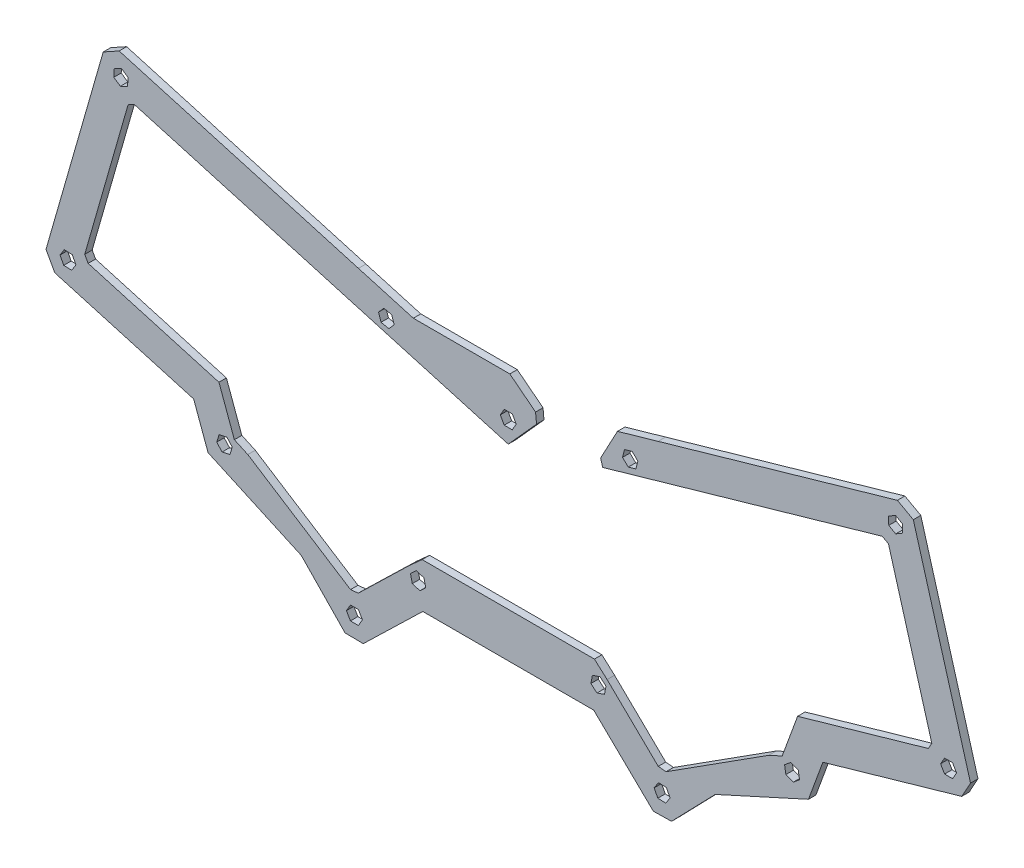
SolidWorks part; units mm, degrees
ref_plane "Plan de face" through (0, 0, 0) normal (0, 0, 1) x (1, 0, 0)
ref_plane "Plan de dessus" through (0, 0, 0) normal (0, 1, 0) x (1, 0, 0)
ref_plane "Plan de droite" through (0, 0, 0) normal (1, 0, 0) x (0, 0, -1)
sketch "Esquisse1" plane through (0, 0, 0) normal (0, 0, 1) x (1, 0, 0)
  line L0 (-121.6461, -32.0475) -> (-108.1875, -28.1884) construction
  line L1 (-108.1875, -28.1884) -> (-104.3283, -41.647) construction
  line L2 (-104.3283, -41.647) -> (-117.7869, -45.5062) construction
  line L3 (-117.7869, -45.5062) -> (-121.6461, -32.0475) construction
  line L4 (-100.1763, -37.9855) -> (-104.0355, -24.5269) construction
  line L5 (-104.0355, -24.5269) -> (-90.5769, -20.6677) construction
  line L6 (-90.5769, -20.6677) -> (-86.7177, -34.1263) construction
  line L7 (-86.7177, -34.1263) -> (-100.1763, -37.9855) construction
  line L8 (-82.5657, -30.4649) -> (-86.4249, -17.0063) construction
  line L9 (-86.4249, -17.0063) -> (-72.9663, -13.1471) construction
  line L10 (-72.9663, -13.1471) -> (-69.1071, -26.6057) construction
  line L11 (-69.1071, -26.6057) -> (-82.5657, -30.4649) construction
  line L12 (-63.6458, -27.5106) -> (-67.505, -14.0519) construction
  line L13 (-67.505, -14.0519) -> (-54.0463, -10.1927) construction
  line L14 (-54.0463, -10.1927) -> (-50.1872, -23.6514) construction
  line L15 (-50.1872, -23.6514) -> (-63.6458, -27.5106) construction
  line L16 (-44.0711, -26.8394) -> (-47.9303, -13.3808) construction
  line L17 (-47.9303, -13.3808) -> (-34.4717, -9.5216) construction
  line L18 (-34.4717, -9.5216) -> (-30.6125, -22.9802) construction
  line L19 (-30.6125, -22.9802) -> (-44.0711, -26.8394) construction
  line L20 (-25.8054, -21.6018) -> (-29.6646, -8.1432) construction
  line L21 (-29.6646, -8.1432) -> (-16.206, -4.284)
  line L22 (-16.206, -4.284) -> (-12.3468, -17.7426)
  line L23 (-12.3468, -17.7426) -> (-25.8054, -21.6018) construction
  line L24 (-116.4086, -50.3128) -> (-102.95, -46.4536) construction
  line L25 (-102.95, -46.4536) -> (-99.0908, -59.9122) construction
  line L26 (-99.0908, -59.9122) -> (-112.5494, -63.7714) construction
  line L27 (-112.5494, -63.7714) -> (-116.4086, -50.3128) construction
  line L28 (-98.798, -42.7922) -> (-85.3394, -38.933) construction
  line L29 (-85.3394, -38.933) -> (-81.4802, -52.3916) construction
  line L30 (-81.4802, -52.3916) -> (-94.9388, -56.2508) construction
  line L31 (-94.9388, -56.2508) -> (-98.798, -42.7922) construction
  line L32 (-81.1874, -35.2715) -> (-67.7288, -31.4123) construction
  line L33 (-67.7288, -31.4123) -> (-63.8696, -44.8709) construction
  line L34 (-63.8696, -44.8709) -> (-77.3282, -48.7301) construction
  line L35 (-77.3282, -48.7301) -> (-81.1874, -35.2715) construction
  line L36 (-62.2675, -32.3172) -> (-48.8089, -28.458) construction
  line L37 (-48.8089, -28.458) -> (-44.9497, -41.9166) construction
  line L38 (-44.9497, -41.9166) -> (-58.4083, -45.7758) construction
  line L39 (-58.4083, -45.7758) -> (-62.2675, -32.3172) construction
  line L40 (-42.6928, -31.646) -> (-29.2342, -27.7869) construction
  line L41 (-29.2342, -27.7869) -> (-25.375, -41.2455) construction
  line L42 (-25.375, -41.2455) -> (-38.8336, -45.1047) construction
  line L43 (-38.8336, -45.1047) -> (-42.6928, -31.646) construction
  line L44 (-24.4271, -26.4084) -> (-10.9685, -22.5492) construction
  line L45 (-10.9685, -22.5492) -> (-7.1093, -36.0078) construction
  line L46 (-7.1093, -36.0078) -> (-20.5679, -39.867) construction
  line L47 (-20.5679, -39.867) -> (-24.4271, -26.4084) construction
  line L48 (-19.1896, -44.6737) -> (-5.731, -40.8145) construction
  line L49 (-5.731, -40.8145) -> (-1.8718, -54.2731) construction
  line L50 (-1.8718, -54.2731) -> (-15.3304, -58.1323) construction
  line L51 (-15.3304, -58.1323) -> (-19.1896, -44.6737) construction
  line L52 (-37.4554, -49.9113) -> (-23.9967, -46.0521) construction
  line L53 (-23.9967, -46.0521) -> (-20.1376, -59.5107) construction
  line L54 (-20.1376, -59.5107) -> (-33.5962, -63.3699) construction
  line L55 (-33.5962, -63.3699) -> (-37.4554, -49.9113) construction
  line L56 (-57.03, -50.5825) -> (-43.5714, -46.7233) construction
  line L57 (-43.5714, -46.7233) -> (-39.7122, -60.1819) construction
  line L58 (-39.7122, -60.1819) -> (-53.1708, -64.0411) construction
  line L59 (-53.1708, -64.0411) -> (-57.03, -50.5825) construction
  line L60 (-75.9499, -53.5368) -> (-62.4913, -49.6776) construction
  line L61 (-62.4913, -49.6776) -> (-58.6321, -63.1362) construction
  line L62 (-58.6321, -63.1362) -> (-72.0908, -66.9954) construction
  line L63 (-72.0908, -66.9954) -> (-75.9499, -53.5368) construction
  line L64 (-93.5605, -61.0574) -> (-80.1019, -57.1982) construction
  line L65 (-80.1019, -57.1982) -> (-76.2427, -70.6569) construction
  line L66 (-76.2427, -70.6569) -> (-89.7013, -74.516) construction
  line L67 (-89.7013, -74.516) -> (-93.5605, -61.0574) construction
  line L68 (-111.1711, -68.5781) -> (-97.7125, -64.7189) construction
  line L69 (-97.7125, -64.7189) -> (-93.8533, -78.1775) construction
  line L70 (-93.8533, -78.1775) -> (-107.3119, -82.0367) construction
  line L71 (-107.3119, -82.0367) -> (-111.1711, -68.5781) construction
  line L72 (-79.0181, -77.3048) -> (-65.5595, -73.4456) construction
  line L73 (-65.5595, -73.4456) -> (-61.7003, -86.9042) construction
  line L74 (-61.7003, -86.9042) -> (-75.1589, -90.7634) construction
  line L75 (-75.1589, -90.7634) -> (-79.0181, -77.3048) construction
  line L76 (-99.4001, -88.1351) -> (-87.3916, -80.9362) construction
  line L77 (-87.3916, -80.9362) -> (-80.1927, -92.9448) construction
  line L78 (-80.1927, -92.9448) -> (-92.2012, -100.1436) construction
  line L79 (-92.2012, -100.1436) -> (-99.4001, -88.1351) construction
  line L80 (-120.0498, -100.4367) -> (-110.317, -90.3719) construction
  line L81 (-110.317, -90.3719) -> (-100.2522, -100.1047) construction
  line L82 (-100.2522, -100.1047) -> (-109.985, -110.1695) construction
  line L83 (-109.985, -110.1695) -> (-120.0498, -100.4367) construction
  line L86 (0.634, -55.7756) -> (-52.9527, -71.1413) construction
  line L89 (-59.2205, -88.2424) -> (-52.9527, -71.1413) construction
  line L96 (-93.4066, -103.0586) -> (-59.4637, -88.3612) construction
  line L97 (-105.418, -115.2057) -> (-93.9754, -103.3509) construction
  line L98 (-126.5332, -96.9919) -> (-107.5003, -115.385) construction
  line L99 (-167.7972, -50.1766) -> (-183.2082, -64.014) construction
  line L100 (-106.3822, -25.4572) -> (-123.6848, -30.4187) construction
  line L101 (-72.1178, -10.6906) -> (-88.4663, -15.3784) construction
  line L102 (-53.2337, -7.6163) -> (-70.5393, -12.5786) construction
  line L103 (-33.6604, -6.9452) -> (-50.9661, -11.9075) construction
  line L104 (-15.3965, -1.7081) -> (-31.745, -6.396) construction
  line L105 (0.5403, -55.2132) -> (-14.6896, -2.0999) construction
  line L106 (-16.199, -60.6113) -> (0.1495, -55.9235) construction
  line L107 (-52.7198, -71.0835) -> (-18.1144, -61.1606) construction
  line L108 (-59.1184, -88.0534) -> (-52.9674, -71.2752) construction
  line L109 (-183.2082, -64.014) -> (-173.1824, -64.9357) construction
  line L113 (-102.2678, -134.438) -> (-84.7238, -116.3191) construction
  line L114 (-84.7238, -116.3191) -> (-47.2969, -99.2981) construction
  line L115 (-47.2969, -99.2981) -> (-41.4917, -83.4594) construction
  line L116 (14.3812, -67.4381) -> (-41.4917, -83.4594) construction
  line L117 (17.8093, -61.2536) -> (-5.1371, 18.7701) construction
  line L122 (-11.3217, 22.1985) -> (-107.4545, -5.3614) construction
  line L129 (-167.7953, -27.6055) -> (-167.7953, -64.7189) construction
  line L130 (-242.0685, -103.8419) -> (-276.37, -88.2424) construction
  line L131 (-229.5108, -116.8112) -> (-242.0685, -103.8419) construction
  line L138 (-208.9328, -96.8551) -> (-229.5108, -116.8112) construction
  line L139 (-225.5107, -79.6567) -> (-208.9328, -96.8551) construction
  line L140 (-109.3352, -134.5492) -> (-102.2678, -134.438) construction
  line L142 (-5.1371, 18.7701) -> (-11.3217, 22.1985) construction
  line L143 (-211.4691, -30.6868) -> (-225.5107, -79.6567) construction
  line L147 (-114.18, -7.2899) -> (-107.4545, -5.3614) construction
  line L148 (-114.18, -7.2899) -> (-123.7936, -10.0465) construction
  line L154 (-4.3102, 15.8863) -> (-127.3606, -19.3904) construction
  line L155 (-131.531, -101.8802) -> (-105.9239, -126.7133) construction
  line L156 (-105.9239, -126.7133) -> (-89.4162, -109.6646) construction
  line L157 (-127.3539, -97.573) -> (-105.9069, -118.3718) construction
  line L158 (-105.9069, -118.3718) -> (-63.5032, -91.2886) construction
  line L159 (-63.5032, -91.2886) -> (-58.4256, -88.9794) construction
  line L160 (-58.4256, -88.9794) -> (-52.1886, -71.9625) construction
  line L161 (1.8709, -56.4612) -> (-52.1886, -71.9625) construction
  line L162 (1.8709, -56.4612) -> (-14.1861, -0.4639) construction
  line L163 (-14.1861, -0.4639) -> (-50.7166, -10.9388) construction
  line L164 (-50.7166, -10.9388) -> (-52.026, -6.3725) construction
  line L165 (-52.026, -6.3725) -> (-70.2913, -11.61) construction
  line L166 (-70.2913, -11.61) -> (-70.911, -9.4488) construction
  line L167 (-70.911, -9.4488) -> (-90.1377, -14.9608) construction
  line L168 (-90.1377, -14.9608) -> (-89.5177, -17.1231) construction
  line L169 (-89.5177, -17.1231) -> (-107.783, -22.3606) construction
  line L170 (-107.783, -22.3606) -> (-107.0938, -24.7639) construction
  line L171 (-107.0938, -24.7639) -> (-125.3583, -30.0011) construction
  line L172 (-125.3583, -30.0011) -> (-111.0411, -79.9324) construction
  line L173 (-110.7998, -78.9627) -> (-127.3777, -96.1611) construction
  line L174 (-89.4162, -109.6646) -> (-53.6562, -93.4017) construction
  line L175 (-53.6562, -93.4017) -> (-47.6042, -76.8897) construction
  line L176 (9.2923, -60.5749) -> (-47.6042, -76.8897) construction
  line L177 (9.2923, -60.5749) -> (-12.0005, 13.6817) construction
  line L178 (-229.7336, -25.4495) -> (-211.4691, -30.6868) construction
  line L179 (-229.0444, -23.0462) -> (-229.7336, -25.4495) construction
  line L180 (-173.1824, -64.9357) -> (-167.7972, -60.1004) construction
  line L181 (-247.3097, -17.8087) -> (-229.0444, -23.0462) construction
  line L185 (17.8093, -61.2536) -> (14.3812, -67.4381) construction
  line L186 (-183.2987, -65.7677) -> (-173.2729, -66.6895) construction
  line L187 (-173.2729, -66.6895) -> (-167.8052, -74.7882) construction
  line L190 (-246.6897, -15.6465) -> (-247.3097, -17.8087) construction
  line L191 (-263.9939, -10.6857) -> (-246.6897, -15.6465) construction
  line L192 (-264.6136, -12.8469) -> (-263.9939, -10.6857) construction
  line L193 (-282.8789, -7.6094) -> (-264.6136, -12.8469) construction
  line L194 (-284.1883, -12.1757) -> (-282.8789, -7.6094) construction
  line L195 (-320.7188, -1.7008) -> (-284.1883, -12.1757) construction
  line L196 (-336.2245, -55.7756) -> (-320.7188, -1.7008) construction
  line L197 (-183.2987, -65.7677) -> (-167.8052, -88.0782) construction
  line L198 (-181.8414, -71.5322) -> (-174.8684, -81.0171) construction
  line L199 (-174.8684, -81.0171) -> (-178.3549, -83.9622) construction
  line L200 (-344.8828, -60.5749) -> (-323.5901, 13.6817) construction
  line L201 (-344.8828, -60.5749) -> (-287.9863, -76.8897) construction
  line L202 (-281.9343, -93.4017) -> (-287.9863, -76.8897) construction
  line L203 (-246.1743, -109.6646) -> (-281.9343, -93.4017) construction
  line L204 (-224.7907, -78.9627) -> (-208.2128, -96.1611) construction
  line L205 (-210.2322, -30.0011) -> (-224.5494, -79.9324) construction
  line L206 (-228.4967, -24.7639) -> (-210.2322, -30.0011) construction
  line L207 (-227.8075, -22.3606) -> (-228.4967, -24.7639) construction
  line L208 (-246.0728, -17.1231) -> (-227.8075, -22.3606) construction
  line L209 (-245.4528, -14.9608) -> (-246.0728, -17.1231) construction
  line L210 (-264.6796, -9.4488) -> (-245.4528, -14.9608) construction
  line L211 (-265.2993, -11.61) -> (-264.6796, -9.4488) construction
  line L212 (-283.5645, -6.3725) -> (-265.2993, -11.61) construction
  line L213 (-284.8739, -10.9388) -> (-283.5645, -6.3725) construction
  line L217 (0.634, -55.7756) -> (-14.8717, -1.7008) construction
  line L220 (-14.8717, -1.7008) -> (-51.4022, -12.1757) construction
  line L221 (-51.4022, -12.1757) -> (-52.7116, -7.6094) construction
  line L222 (-52.7116, -7.6094) -> (-70.9769, -12.8469) construction
  line L223 (-70.9769, -12.8469) -> (-71.5966, -10.6857) construction
  line L224 (-71.5966, -10.6857) -> (-88.9008, -15.6465) construction
  line L225 (-88.9008, -15.6465) -> (-88.2808, -17.8087) construction
  line L226 (-88.2808, -17.8087) -> (-106.5461, -23.0462) construction
  line L227 (-106.5461, -23.0462) -> (-105.8569, -25.4495) construction
  line L228 (-105.8569, -25.4495) -> (-124.1214, -30.6868) construction
  line L231 (-124.1214, -30.6868) -> (-110.0799, -79.6567) construction
  line L232 (-110.0799, -79.6567) -> (-126.6577, -96.8551) construction
  line L233 (-126.6577, -96.8551) -> (-106.0797, -116.8112) construction
  line L234 (-106.0797, -116.8112) -> (-93.522, -103.8419) construction
  line L235 (-93.522, -103.8419) -> (-59.2205, -88.2424) construction
  line L236 (-321.4044, -0.4639) -> (-284.8739, -10.9388) construction
  line L237 (-337.4614, -56.4612) -> (-321.4044, -0.4639) construction
  line L238 (-337.4614, -56.4612) -> (-283.4019, -71.9625) construction
  line L239 (-277.1649, -88.9794) -> (-283.4019, -71.9625) construction
  line L240 (-272.0873, -91.2886) -> (-277.1649, -88.9794) construction
  line L241 (-229.6837, -118.3718) -> (-272.0873, -91.2886) construction
  line L242 (-208.2366, -97.573) -> (-229.6837, -118.3718) construction
  line L243 (-229.6666, -126.7133) -> (-246.1743, -109.6646) construction
  line L244 (-204.0596, -101.8802) -> (-229.6666, -126.7133) construction
  line L245 (-331.2803, 15.8863) -> (-208.2299, -19.3904) construction
  line L246 (-178.3549, -83.9622) -> (-185.8788, -75.0552) construction
  line L247 (-185.8788, -75.0552) -> (-181.8414, -71.5322) construction
  line L248 (-176.7625, -46.6332) -> (-185.5498, -54.5291) construction
  line L249 (-185.5498, -54.5291) -> (-181.1562, -59.4188) construction
  line L250 (-181.1562, -59.4188) -> (-172.3689, -51.5229) construction
  line L251 (-276.4721, -88.0534) -> (-282.6232, -71.2752) construction
  line L252 (-282.8707, -71.0835) -> (-317.4761, -61.1606) construction
  line L253 (-319.3915, -60.6113) -> (-335.74, -55.9235) construction
  line L254 (-336.1309, -55.2132) -> (-320.9009, -2.0999) construction
  line L255 (-320.194, -1.7081) -> (-303.8455, -6.396) construction
  line L256 (-301.9301, -6.9452) -> (-284.6245, -11.9075) construction
  line L257 (-282.3568, -7.6163) -> (-265.0512, -12.5786) construction
  line L258 (-263.4727, -10.6906) -> (-247.1242, -15.3784) construction
  line L259 (-229.2083, -25.4572) -> (-211.9057, -30.4187) construction
  line L260 (-172.3689, -51.5229) -> (-176.7625, -46.6332) construction
  line L261 (-209.0573, -96.9919) -> (-228.0902, -115.385) construction
  line L262 (-230.1725, -115.2057) -> (-241.6151, -103.3509) construction
  line L263 (-242.1839, -103.0586) -> (-276.1268, -88.3612) construction
  line L264 (-276.37, -88.2424) -> (-282.6379, -71.1413) construction
  line L265 (-336.2245, -55.7756) -> (-282.6379, -71.1413) construction
  line L268 (-353.3998, -61.2536) -> (-349.9717, -67.4381) construction
  line L274 (-221.4105, -7.2899) -> (-206.0252, -11.7015) construction
  line L275 (-221.4105, -7.2899) -> (-228.136, -5.3614) construction
  line L276 (-330.4534, 18.7701) -> (-324.2688, 22.1985) construction
  line L277 (-226.2553, -134.5492) -> (-233.3227, -134.438) construction
  line L281 (-324.2688, 22.1985) -> (-228.136, -5.3614) construction
  line L282 (-353.3998, -61.2536) -> (-330.4534, 18.7701) construction
  line L283 (-349.9717, -67.4381) -> (-294.0988, -83.4594) construction
  line L284 (-288.2936, -99.2981) -> (-294.0988, -83.4594) construction
  line L285 (-250.8667, -116.3191) -> (-288.2936, -99.2981) construction
  line L286 (-233.3227, -134.438) -> (-250.8667, -116.3191) construction
  line L288 (-225.6055, -110.1695) -> (-215.5407, -100.4367) construction
  line L289 (-235.3383, -100.1047) -> (-225.6055, -110.1695) construction
  line L290 (-225.2735, -90.3719) -> (-235.3383, -100.1047) construction
  line L291 (-215.5407, -100.4367) -> (-225.2735, -90.3719) construction
  line L292 (-243.3893, -100.1436) -> (-236.1904, -88.1351) construction
  line L293 (-255.3978, -92.9448) -> (-243.3893, -100.1436) construction
  line L294 (-248.1989, -80.9362) -> (-255.3978, -92.9448) construction
  line L295 (-236.1904, -88.1351) -> (-248.1989, -80.9362) construction
  line L296 (-260.4316, -90.7634) -> (-256.5724, -77.3048) construction
  line L297 (-273.8902, -86.9042) -> (-260.4316, -90.7634) construction
  line L298 (-270.031, -73.4456) -> (-273.8902, -86.9042) construction
  line L299 (-256.5724, -77.3048) -> (-270.031, -73.4456) construction
  line L300 (-228.2786, -82.0367) -> (-224.4194, -68.5781) construction
  line L301 (-241.7372, -78.1775) -> (-228.2786, -82.0367) construction
  line L302 (-237.878, -64.7189) -> (-241.7372, -78.1775) construction
  line L303 (-224.4194, -68.5781) -> (-237.878, -64.7189) construction
  line L304 (-245.8892, -74.516) -> (-242.03, -61.0574) construction
  line L305 (-259.3478, -70.6569) -> (-245.8892, -74.516) construction
  line L306 (-255.4886, -57.1982) -> (-259.3478, -70.6569) construction
  line L307 (-242.03, -61.0574) -> (-255.4886, -57.1982) construction
  line L308 (-263.4998, -66.9954) -> (-259.6406, -53.5368) construction
  line L309 (-276.9584, -63.1362) -> (-263.4998, -66.9954) construction
  line L310 (-273.0992, -49.6776) -> (-276.9584, -63.1362) construction
  line L311 (-259.6406, -53.5368) -> (-273.0992, -49.6776)
  line L312 (-282.4197, -64.0411) -> (-278.5605, -50.5825) construction
  line L313 (-295.8783, -60.1819) -> (-282.4197, -64.0411) construction
  line L314 (-292.0191, -46.7233) -> (-295.8783, -60.1819) construction
  line L315 (-278.5605, -50.5825) -> (-292.0191, -46.7233) construction
  line L316 (-301.9944, -63.3699) -> (-298.1352, -49.9113) construction
  line L317 (-315.453, -59.5107) -> (-301.9944, -63.3699) construction
  line L318 (-311.5938, -46.0521) -> (-315.453, -59.5107) construction
  line L319 (-298.1352, -49.9113) -> (-311.5938, -46.0521) construction
  line L320 (-320.2601, -58.1323) -> (-316.4009, -44.6737) construction
  line L321 (-333.7187, -54.2731) -> (-320.2601, -58.1323) construction
  line L322 (-329.8595, -40.8145) -> (-333.7187, -54.2731) construction
  line L323 (-316.4009, -44.6737) -> (-329.8595, -40.8145) construction
  line L324 (-315.0226, -39.867) -> (-311.1634, -26.4084) construction
  line L325 (-328.4812, -36.0078) -> (-315.0226, -39.867) construction
  line L326 (-324.622, -22.5492) -> (-328.4812, -36.0078) construction
  line L327 (-311.1634, -26.4084) -> (-324.622, -22.5492) construction
  line L328 (-296.7569, -45.1047) -> (-292.8977, -31.646) construction
  line L329 (-310.2155, -41.2455) -> (-296.7569, -45.1047) construction
  line L330 (-306.3563, -27.7869) -> (-310.2155, -41.2455) construction
  line L331 (-292.8977, -31.646) -> (-306.3563, -27.7869) construction
  line L332 (-277.1822, -45.7758) -> (-273.323, -32.3172) construction
  line L333 (-290.6408, -41.9166) -> (-277.1822, -45.7758) construction
  line L334 (-286.7817, -28.458) -> (-290.6408, -41.9166) construction
  line L335 (-273.323, -32.3172) -> (-286.7817, -28.458) construction
  line L336 (-258.2623, -48.7301) -> (-254.4031, -35.2715) construction
  line L337 (-271.7209, -44.8709) -> (-258.2623, -48.7301) construction
  line L338 (-267.8617, -31.4123) -> (-271.7209, -44.8709) construction
  line L339 (-254.4031, -35.2715) -> (-267.8617, -31.4123) construction
  line L340 (-240.6517, -56.2508) -> (-236.7925, -42.7922) construction
  line L341 (-254.1103, -52.3916) -> (-240.6517, -56.2508) construction
  line L342 (-250.2511, -38.933) -> (-254.1103, -52.3916) construction
  line L343 (-236.7925, -42.7922) -> (-250.2511, -38.933) construction
  line L344 (-223.0411, -63.7714) -> (-219.1819, -50.3128) construction
  line L345 (-236.4997, -59.9122) -> (-223.0411, -63.7714) construction
  line L346 (-232.6405, -46.4536) -> (-236.4997, -59.9122) construction
  line L347 (-219.1819, -50.3128) -> (-232.6405, -46.4536) construction
  line L348 (-323.2438, -17.7426) -> (-309.7851, -21.6018) construction
  line L349 (-319.3846, -4.284) -> (-323.2438, -17.7426) construction
  line L350 (-305.926, -8.1432) -> (-319.3846, -4.284) construction
  line L351 (-309.7851, -21.6018) -> (-305.926, -8.1432) construction
  line L352 (-304.978, -22.9802) -> (-291.5194, -26.8394) construction
  line L353 (-301.1188, -9.5216) -> (-304.978, -22.9802) construction
  line L354 (-287.6602, -13.3808) -> (-301.1188, -9.5216) construction
  line L355 (-291.5194, -26.8394) -> (-287.6602, -13.3808) construction
  line L356 (-285.4034, -23.6514) -> (-271.9448, -27.5106) construction
  line L357 (-281.5442, -10.1927) -> (-285.4034, -23.6514) construction
  line L358 (-268.0856, -14.0519) -> (-281.5442, -10.1927) construction
  line L359 (-271.9448, -27.5106) -> (-268.0856, -14.0519) construction
  line L360 (-266.4834, -26.6057) -> (-253.0248, -30.4649) construction
  line L361 (-262.6242, -13.1471) -> (-266.4834, -26.6057) construction
  line L362 (-249.1656, -17.0063) -> (-262.6242, -13.1471) construction
  line L363 (-253.0248, -30.4649) -> (-249.1656, -17.0063) construction
  line L364 (-248.8728, -34.1263) -> (-235.4142, -37.9855) construction
  line L365 (-245.0136, -20.6677) -> (-248.8728, -34.1263) construction
  line L366 (-231.555, -24.5269) -> (-245.0136, -20.6677) construction
  line L367 (-235.4142, -37.9855) -> (-231.555, -24.5269) construction
  line L368 (-217.8036, -45.5062) -> (-213.9444, -32.0475) construction
  line L369 (-231.2622, -41.647) -> (-217.8036, -45.5062) construction
  line L370 (-227.4031, -28.1884) -> (-231.2622, -41.647) construction
  line L371 (-213.9444, -32.0475) -> (-227.4031, -28.1884) construction
  line L372 (-226.2553, -134.5492) -> (-202.2968, -111.3509) construction
  line L373 (-109.3352, -134.5492) -> (-133.2937, -111.3509) construction
  line L374 (-141.5559, -103.3509) -> (-194.0347, -103.3509) construction
  line L375 (-167.7972, -50.1766) -> (-152.3861, -64.014) construction
  line L376 (-162.4119, -64.9357) -> (-167.7972, -60.1004) construction
  line L377 (-162.3376, -66.6895) -> (-167.8052, -74.7882) construction
  line L378 (-152.3118, -65.7677) -> (-167.8052, -88.0782) construction
  line L379 (-163.2254, -51.5229) -> (-158.8318, -46.6332) construction
  line L380 (-154.4381, -59.4188) -> (-163.2254, -51.5229) construction
  line L381 (-150.0445, -54.5291) -> (-154.4381, -59.4188) construction
  line L382 (-158.8318, -46.6332) -> (-150.0445, -54.5291) construction
  line L383 (-149.7316, -75.0552) -> (-153.7691, -71.5322) construction
  line L384 (-157.2555, -83.9622) -> (-149.7316, -75.0552) construction
  line L385 (-160.742, -81.0171) -> (-157.2555, -83.9622) construction
  line L386 (-153.7691, -71.5322) -> (-160.742, -81.0171) construction
  line L387 (-152.3118, -65.7677) -> (-162.3376, -66.6895) construction
  line L388 (-152.3861, -64.014) -> (-162.4119, -64.9357) construction
  line L389 (-206.0252, -11.7015) -> (-129.5654, -11.7015) construction
  line L390 (-119.0708, -62.7964) -> (-130.6498, -22.4155) construction
  line L391 (-123.5545, -47.16) -> (-127.4136, -33.7014) construction
  line L392 (-120.442, -65.2702) -> (-138.2688, -70.3819) construction
  line L393 (-140.7426, -69.0107) -> (-154.4194, -21.3141) construction
  line L394 (-167.1758, -11.7015) -> (-206.0252, -11.7015) construction
  line L395 (-156.8153, -19.5087) -> (-167.1758, -11.7015) construction
  line L396 (-123.7936, -10.0465) -> (-130.6498, -22.4155) construction
  line L397 (-138.2688, -70.3819) -> (-140.7426, -69.0107) construction
  line L398 (-119.0708, -62.7964) -> (-120.442, -65.2702) construction
  line L399 (-129.5654, -11.7015) -> (-123.7936, -10.0465) construction
  line L400 (-207.5404, -98.2908) -> (-228.1196, -118.248)
  line L401 (-231.2409, -118.5638) -> (-272.5658, -92.1695)
  line L402 (-272.5658, -92.1695) -> (-277.9598, -89.7165)
  line L403 (-277.9598, -89.7165) -> (-284.166, -72.7837)
  line L404 (-336.7758, -57.6981) -> (-284.166, -72.7837)
  line L405 (-338.147, -55.2243) -> (-320.7131, 5.5749)
  line L406 (-223.5881, -80.208) -> (-202.439, -93.7159) construction
  line L407 (-202.439, -93.7159) -> (-207.5404, -98.2908)
  line L408 (-17.3512, 6.9463) -> (-127.905, -24.7479)
  line L409 (2.5565, -55.2243) -> (-14.8774, 5.5749)
  line L410 (-318.2393, 6.9463) -> (-167.7953, -36.1838)
  line L411 (1.1853, -57.6981) -> (-51.4245, -72.7837)
  line L412 (-57.6307, -89.7165) -> (-51.4245, -72.7837)
  line L413 (-63.0247, -92.1695) -> (-57.6307, -89.7165)
  line L414 (-104.3497, -118.5638) -> (-63.0247, -92.1695)
  line L415 (-207.6856, -24.7479) -> (-223.5881, -80.208) construction
  line L416 (-338.6983, -57.1468) -> (-322.0901, 0.773) construction
  line L417 (-265.3652, -8.212) -> (-244.2159, -14.2752) construction
  line L418 (-208.9953, -29.3155) -> (-223.5881, -80.208) construction
  line L419 (-227.2598, -24.0783) -> (-208.9953, -29.3155) construction
  line L420 (-226.5706, -21.6749) -> (-227.2598, -24.0783) construction
  line L421 (-244.8359, -16.4375) -> (-226.5706, -21.6749) construction
  line L422 (-244.2159, -14.2752) -> (-244.8359, -16.4375) construction
  line L423 (-265.9849, -10.3731) -> (-265.3652, -8.212) construction
  line L424 (-284.2502, -5.1356) -> (-265.9849, -10.3731) construction
  line L425 (-285.5595, -9.7019) -> (-284.2502, -5.1356) construction
  line L426 (-322.0901, 0.773) -> (-285.5595, -9.7019) construction
  line L427 (-128.0501, -98.2908) -> (-107.4709, -118.248)
  line L428 (-133.1515, -93.7159) -> (-128.0501, -98.2908)
  line L429 (-127.905, -24.7479) -> (-167.7953, -36.1862) construction
  line L430 (-129.8233, -25.2979) -> (-130.6498, -22.4155)
  line L431 (-202.439, -93.7159) -> (-133.1515, -93.7159)
  line L432 (-167.7953, -36.1838) -> (-156.4257, -23.5445)
  line L433 (-129.8233, -25.2979) -> (-127.905, -24.7479)
  line L434 (-156.4257, -23.5445) -> (-156.8153, -19.5087)
  line L435 (-320.7131, 5.5749) -> (-318.2393, 6.9463)
  line L436 (-338.6983, -57.1468) -> (-284.166, -72.7837) construction
  line L437 (-338.147, -55.2243) -> (-336.7758, -57.6981)
  line L438 (-207.5404, -98.2908) -> (-229.5553, -119.6404) construction
  line L439 (-229.5553, -119.6404) -> (-272.5658, -92.1695) construction
  line L440 (-228.1196, -118.248) -> (-231.2409, -118.5638)
  line L441 (-107.4709, -118.248) -> (-104.3497, -118.5638)
  line L442 (2.5565, -55.2243) -> (1.1853, -57.6981)
  line L443 (-14.8774, 5.5749) -> (-17.3512, 6.9463)
  line L444 (-133.2937, -111.3509) -> (-202.2968, -111.3509) construction
  line L445 (-214.6968, -14.5277) -> (-217.8401, -13.8763)
  line L446 (-217.8401, -13.8763) -> (-219.9759, -16.2728)
  line L447 (-219.9759, -16.2728) -> (-218.9683, -19.3206)
  line L448 (-218.9683, -19.3206) -> (-215.8251, -19.972)
  line L449 (-215.8251, -19.972) -> (-213.6893, -17.5755)
  line L450 (-213.6893, -17.5755) -> (-214.6968, -14.5277)
  line L451 (-166.1757, -24.834) -> (-169.3858, -24.8172)
  line L452 (-169.3858, -24.8172) -> (-171.0053, -27.5888)
  line L453 (-171.0053, -27.5888) -> (-169.4148, -30.3771)
  line L454 (-169.4148, -30.3771) -> (-166.2047, -30.3939)
  line L455 (-166.2047, -30.3939) -> (-164.5852, -27.6223)
  line L456 (-164.5852, -27.6223) -> (-166.1757, -24.834)
  line L457 (-115.6722, -16.0395) -> (-117.9812, -13.8095)
  line L458 (-117.9812, -13.8095) -> (-121.0669, -14.6941)
  line L459 (-121.0669, -14.6941) -> (-121.8437, -17.8088)
  line L460 (-121.8437, -17.8088) -> (-119.5347, -20.0388)
  line L461 (-119.5347, -20.0388) -> (-116.4489, -19.1542)
  line L462 (-116.4489, -19.1542) -> (-115.6722, -16.0395)
  line L463 (-9.2401, 15.3202) -> (-12.0393, 16.8915)
  line L464 (-12.0393, 16.8915) -> (-14.7996, 15.253)
  line L465 (-14.7996, 15.253) -> (-14.7608, 12.0431)
  line L466 (-14.7608, 12.0431) -> (-11.9616, 10.4718)
  line L467 (-11.9616, 10.4718) -> (-9.2013, 12.1103)
  line L468 (-9.2013, 12.1103) -> (-9.2401, 15.3202)
  line L469 (12.5024, -60.5749) -> (10.8973, -57.7949)
  line L470 (10.8973, -57.7949) -> (7.6873, -57.7949)
  line L471 (7.6873, -57.7949) -> (6.0822, -60.5749)
  line L472 (6.0822, -60.5749) -> (7.6873, -63.3549)
  line L473 (7.6873, -63.3549) -> (10.8973, -63.3549)
  line L474 (10.8973, -63.3549) -> (12.5024, -60.5749)
  line L475 (-50.6498, -94.5269) -> (-51.1786, -91.3606)
  line L476 (-51.1786, -91.3606) -> (-54.185, -90.2355)
  line L477 (-54.185, -90.2355) -> (-56.6626, -92.2765)
  line L478 (-56.6626, -92.2765) -> (-56.1338, -95.4427)
  line L479 (-56.1338, -95.4427) -> (-53.1274, -96.5679)
  line L480 (-53.1274, -96.5679) -> (-50.6498, -94.5269)
  line L481 (-104.4402, -129.5599) -> (-102.7168, -126.8517)
  line L482 (-102.7168, -126.8517) -> (-104.2006, -124.0051)
  line L483 (-104.2006, -124.0051) -> (-107.4076, -123.8667)
  line L484 (-107.4076, -123.8667) -> (-109.131, -126.575)
  line L485 (-109.131, -126.575) -> (-107.6473, -129.4216)
  line L486 (-107.6473, -129.4216) -> (-104.4402, -129.5599)
  line L487 (-132.1348, -105.033) -> (-129.1025, -103.9795)
  line L488 (-129.1025, -103.9795) -> (-128.4987, -100.8268)
  line L489 (-128.4987, -100.8268) -> (-130.9271, -98.7274)
  line L490 (-130.9271, -98.7274) -> (-133.9594, -99.7809)
  line L491 (-133.9594, -99.7809) -> (-134.5633, -102.9336)
  line L492 (-134.5633, -102.9336) -> (-132.1348, -105.033)
  line L493 (-200.9863, -102.8073) -> (-201.7201, -99.6822)
  line L494 (-201.7201, -99.6822) -> (-204.7933, -98.7551)
  line L495 (-204.7933, -98.7551) -> (-207.1328, -100.9531)
  line L496 (-207.1328, -100.9531) -> (-206.3991, -104.0782)
  line L497 (-206.3991, -104.0782) -> (-203.3258, -105.0053)
  line L498 (-203.3258, -105.0053) -> (-200.9863, -102.8073)
  line L499 (-228.0726, -129.4997) -> (-226.4565, -126.726)
  line L500 (-226.4565, -126.726) -> (-228.0506, -123.9397)
  line L501 (-228.0506, -123.9397) -> (-231.2606, -123.927)
  line L502 (-231.2606, -123.927) -> (-232.8766, -126.7006)
  line L503 (-232.8766, -126.7006) -> (-231.2826, -129.4869)
  line L504 (-231.2826, -129.4869) -> (-228.0726, -129.4997)
  line L505 (-279.7615, -95.7646) -> (-278.8016, -92.7014)
  line L506 (-278.8016, -92.7014) -> (-280.9744, -90.3385)
  line L507 (-280.9744, -90.3385) -> (-284.1072, -91.0388)
  line L508 (-284.1072, -91.0388) -> (-285.0671, -94.102)
  line L509 (-285.0671, -94.102) -> (-282.8943, -96.4649)
  line L510 (-282.8943, -96.4649) -> (-279.7615, -95.7646)
  line L511 (-343.3818, -63.4124) -> (-341.6749, -60.6938)
  line L512 (-341.6749, -60.6938) -> (-343.176, -57.8563)
  line L513 (-343.176, -57.8563) -> (-346.3838, -57.7374)
  line L514 (-346.3838, -57.7374) -> (-348.0907, -60.4561)
  line L515 (-348.0907, -60.4561) -> (-346.5896, -63.2936)
  line L516 (-346.5896, -63.2936) -> (-343.3818, -63.4124)
  line L517 (-323.3776, 16.8847) -> (-326.2578, 15.4671)
  line L518 (-326.2578, 15.4671) -> (-326.4702, 12.2641)
  line L519 (-326.4702, 12.2641) -> (-323.8025, 10.4786)
  line L520 (-323.8025, 10.4786) -> (-320.9224, 11.8962)
  line L521 (-320.9224, 11.8962) -> (-320.7099, 15.0992)
  line L522 (-320.7099, 15.0992) -> (-323.3776, 16.8847)
  line L523 (-141.5559, -111.3509) -> (-194.0347, -111.3509) construction
  line L524 (-167.1758, -11.4015) -> (-205.983, -11.4015)
  line L525 (-221.3278, -7.0015) -> (-205.983, -11.4015)
  line L526 (-221.3278, -7.0015) -> (-228.0533, -5.073)
  line L527 (-324.3056, 22.5211) -> (-228.0533, -5.073)
  line L528 (-330.7075, 18.9723) -> (-324.3056, 22.5211)
  line L529 (-353.7224, -61.2904) -> (-330.7075, 18.9723)
  line L530 (-353.7224, -61.2904) -> (-350.1738, -67.6922)
  line L531 (-350.1738, -67.6922) -> (-294.328, -83.7058)
  line L532 (-288.5321, -99.5192) -> (-294.328, -83.7058)
  line L533 (-251.0427, -116.5686) -> (-288.5321, -99.5192)
  line L534 (-233.4517, -134.736) -> (-251.0427, -116.5686)
  line L535 (-226.1358, -134.8511) -> (-233.4517, -134.736)
  line L536 (-226.1358, -134.8511) -> (-202.1754, -111.6509)
  line L537 (-133.4151, -111.6509) -> (-202.1754, -111.6509)
  line L538 (-109.4547, -134.8511) -> (-133.4151, -111.6509)
  line L539 (-109.4547, -134.8511) -> (-102.1388, -134.736)
  line L540 (-102.1388, -134.736) -> (-84.5479, -116.5686)
  line L541 (-84.5479, -116.5686) -> (-47.0584, -99.5192)
  line L542 (-47.0584, -99.5192) -> (-41.2625, -83.7058)
  line L543 (14.5833, -67.6922) -> (-41.2625, -83.7058)
  line L544 (18.1319, -61.2904) -> (14.5833, -67.6922)
  line L545 (18.1319, -61.2904) -> (-4.883, 18.9723)
  line L546 (-4.883, 18.9723) -> (-11.2849, 22.5211)
  line L547 (-11.2849, 22.5211) -> (-107.5372, -5.073)
  line L548 (-114.2627, -7.0015) -> (-107.5372, -5.073)
  line L549 (-114.2627, -7.0015) -> (-123.8763, -9.7581)
  line L550 (-167.1758, -11.4015) -> (-156.8153, -19.5087)
  line L551 (-130.6498, -22.4155) -> (-123.8763, -9.7581)
  circle A2 centre (-12.0005, 13.6817) radius 1.6 construction
  circle A3 centre (-12.0005, 13.6817) radius 3 construction
  circle A4 centre (-118.7579, -16.9241) radius 1.6 construction
  circle A5 centre (9.2923, -60.5749) radius 1.6 construction
  circle A6 centre (-53.6562, -93.4017) radius 1.6 construction
  circle A7 centre (-105.9239, -126.7133) radius 1.6 construction
  circle A8 centre (-131.531, -101.8802) radius 1.6 construction
  circle A10 centre (-147.4897, -45.973) radius 1.6 construction
  circle A11 centre (-323.5901, 13.6817) radius 3 construction
  circle A12 centre (-188.1008, -45.973) radius 1.6 construction
  circle A14 centre (-204.0596, -101.8802) radius 1.6 construction
  circle A15 centre (-229.6666, -126.7133) radius 1.6 construction
  circle A16 centre (-281.9343, -93.4017) radius 1.6 construction
  circle A17 centre (-344.8828, -60.5749) radius 1.6 construction
  circle A18 centre (-216.8326, -16.9241) radius 1.6 construction
  circle A19 centre (-323.5901, 13.6817) radius 1.6 construction
  circle A20 centre (-167.7953, -27.6055) radius 1.6 construction
  circle A21 centre (-216.8326, -16.9241) radius 2.78 construction
  circle A22 centre (-167.7953, -27.6055) radius 2.78 construction
  circle A23 centre (-118.7579, -16.9241) radius 2.78 construction
  circle A24 centre (-12.0005, 13.6817) radius 2.78 construction
  circle A25 centre (9.2923, -60.5749) radius 2.78 construction
  circle A26 centre (-53.6562, -93.4017) radius 2.78 construction
  circle A27 centre (-105.9239, -126.7133) radius 2.78 construction
  circle A28 centre (-131.531, -101.8802) radius 2.78 construction
  circle A29 centre (-204.0596, -101.8802) radius 2.78 construction
  circle A30 centre (-229.6666, -126.7133) radius 2.78 construction
  circle A31 centre (-281.9343, -93.4017) radius 2.78 construction
  circle A32 centre (-344.8828, -60.5749) radius 2.78 construction
  circle A33 centre (-323.5901, 13.6817) radius 2.78 construction
  point P138 (-167.7953, -27.6055)
  point P139 (-6.5153, 23.5764)
  point P150 (-169.1046, -23.0392)
  point P200 (19.1875, -66.0599)
  point P203 (-141.5228, -71.3355)
  point P204 (-141.5228, 1.5705)
  point P263 (-133.4062, -12.8029)
  point P264 (-118.5195, -64.7189)
  point P283 (-140.1914, -70.9332)
  point P284 (-157.1758, -11.7015)
  point P405 (-354.778, -66.0599)
  point P406 (-329.0752, 23.5764)
  point P423 (-15.4286, 7.4974)
  point P424 (-320.1619, 7.4974)
  point P429 (3.1078, -57.1468)
  point P434 (-106.0352, -119.6404)
  dimension "D3" = 3.2
  dimension "D4" = 6
  dimension "D6" = 3.2
  dimension "D7" = 3.2
  dimension "D8" = 3.2
  dimension "D9" = 3.2
  dimension "D10" = 3.2
  dimension "D16" = 3.2
  dimension "D21" = 5.56
  dimension "D34" = 5.56
  dimension "D2" = 6
  dimension "D5" = 1
  dimension "D11" = 5.56
  dimension "D14" = 5.56
  dimension "D22" = 5.56
  dimension "D26" = 5.56
  dimension "D27" = 5.56
  dimension "D28" = 5.56
  dimension "D29" = 5.56
  dimension "D30" = 5.56
  dimension "D31" = 5.56
  dimension "D32" = 5.56
  dimension "D33" = 5.56
  dimension "D35" = 8
  dimension "D36" = 0.3
extrude "Boss.-Extru.1" add sketch "Esquisse1" along normal blind 3 contours L443 L409 L442 L411 L412 L413 L414 L441 L427 L428 L431 L407 L400 L440 L401 L402 L403 L404 L437 L405 L435 L410 L432 L434 L395 L394 L274 L275 L281 L276 L282 L268 L283 L284 L285 L286 L277 L372 L374 L373 L140 L113 L114 L115 L116 L185 L117 L142 L122 L147 L148
